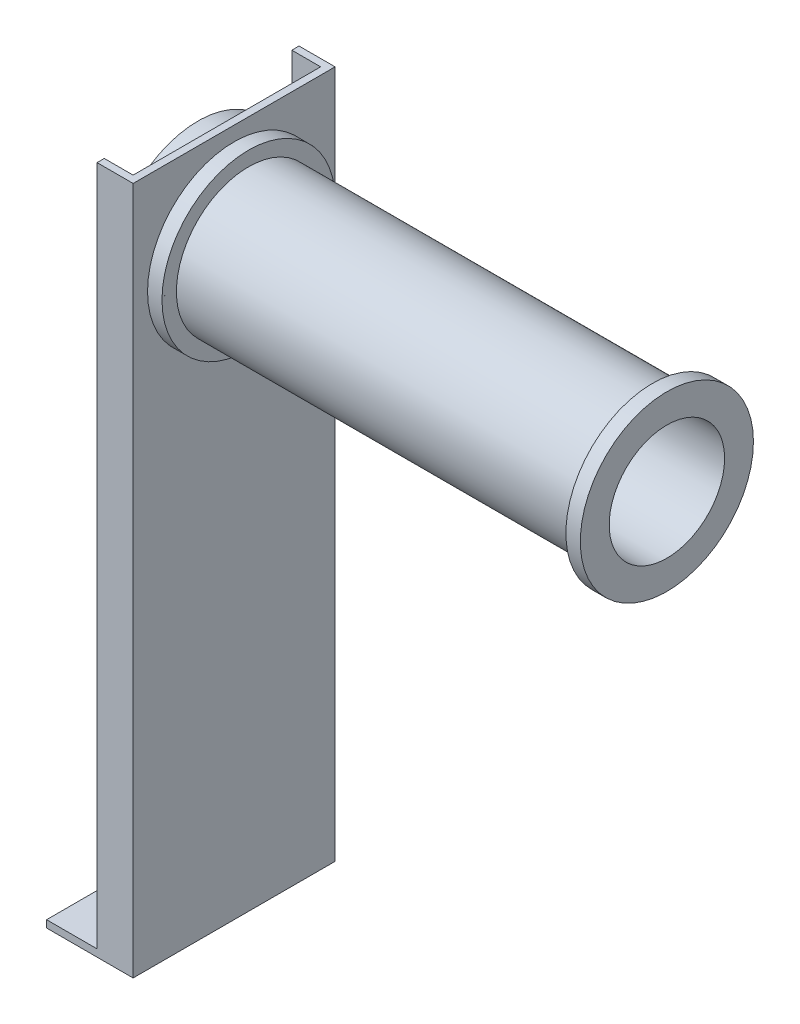
SolidWorks part; units mm, degrees
ref_plane "Front Plane" through (0, 0, 0) normal (0, 0, 1) x (1, 0, 0)
ref_plane "Top Plane" through (0, 0, 0) normal (0, 1, 0) x (1, 0, 0)
ref_plane "Right Plane" through (0, 0, 0) normal (1, 0, 0) x (0, 0, -1)
sketch "Sketch1" plane through (0, 0, 0) normal (1, 0, 0) x (0, 0, -1)
  line L1 (-22.225, -74.93) -> (22.225, -74.93)
  line L2 (-22.225, -74.93) -> (-22.225, 74.93)
  line L3 (-22.225, 74.93) -> (22.225, 74.93)
  line L4 (22.225, -74.93) -> (22.225, 74.93)
  line L5 (-22.225, -74.93) -> (22.225, 74.93) construction
  line L6 (-22.225, 74.93) -> (22.225, -74.93) construction
  point P0 (0, 0)
extrude "Boss-Extrude1" add sketch "Sketch1" along normal blind 1.5875
sketch "Sketch2" plane through (0, 0, 0) normal (-1, 0, 0) x (0, 0, 1)
  line L0 (22.225, -74.93) -> (-22.225, -74.93) construction
  line L1 (22.225, 74.93) -> (20.6375, 74.93)
  line L2 (22.225, 74.93) -> (22.225, -74.93)
  line L3 (22.225, -74.93) -> (20.6375, -74.93)
  line L4 (20.6375, 74.93) -> (20.6375, -74.93)
  line L5 (0, 74.93) -> (0, -74.93) construction
  line L6 (-22.225, 74.93) -> (22.225, 74.93) construction
  line L7 (-22.225, -74.93) -> (-20.6375, -74.93)
  line L8 (-20.6375, 74.93) -> (-20.6375, -74.93)
  line L9 (-22.225, 74.93) -> (-20.6375, 74.93)
  line L10 (-22.225, 74.93) -> (-22.225, -74.93)
extrude "Boss-Extrude2" add sketch "Sketch2" along normal blind 6.35
sketch "Sketch3" plane through (0, -74.93, 0) normal (0, -1, 0) x (1, 0, 0)
  line L2 (1.5875, 22.225) -> (-17.4625, 22.225)
  line L3 (1.5875, 22.225) -> (1.5875, -22.225)
  line L4 (1.5875, -22.225) -> (-17.4625, -22.225)
  line L5 (-17.4625, 22.225) -> (-17.4625, -22.225)
extrude "Boss-Extrude3" add sketch "Sketch3" along normal blind 1.5875
sketch "Sketch4" plane through (1.5875, 0, 0) normal (1, 0, 0) x (0, 0, -1)
  line L0 (0, 74.93) -> (0, 71.755)
  line L1 (22.225, 74.93) -> (-22.225, 74.93) construction
  circle A0 centre (0, 52.705) radius 19.05
extrude "Boss-Extrude4" add sketch "Sketch4" along normal blind 3.175 contours A0
sketch "Sketch5" plane through (4.7625, 0, 0) normal (1, 0, 0) x (0, 0, -1)
  circle A0 centre (0, 52.705) radius 15.875
extrude "Boss-Extrude5" add sketch "Sketch5" along normal blind 88.9
sketch "Sketch6" plane through (93.6625, 0, 0) normal (1, 0, 0) x (0, 0, -1)
  circle A0 centre (0, 52.705) radius 19.05
extrude "Boss-Extrude6" add sketch "Sketch6" along normal blind 3.175
sketch "Sketch7" plane through (0, 0, 0) normal (-1, 0, 0) x (0, 0, 1)
  line L0 (0, 74.93) -> (0, 71.755)
  line L1 (-20.6375, 74.93) -> (20.6375, 74.93) construction
  circle A0 centre (0, 52.705) radius 19.05
extrude "Boss-Extrude7" add sketch "Sketch7" along normal blind 6.35 contours A0
sketch "Sketch8" plane through (96.8375, 0, 0) normal (1, 0, 0) x (0, 0, -1)
  circle A0 centre (0, 52.705) radius 12.7
extrude "Cut-Extrude1" cut sketch "Sketch8" against normal blind 113.665
